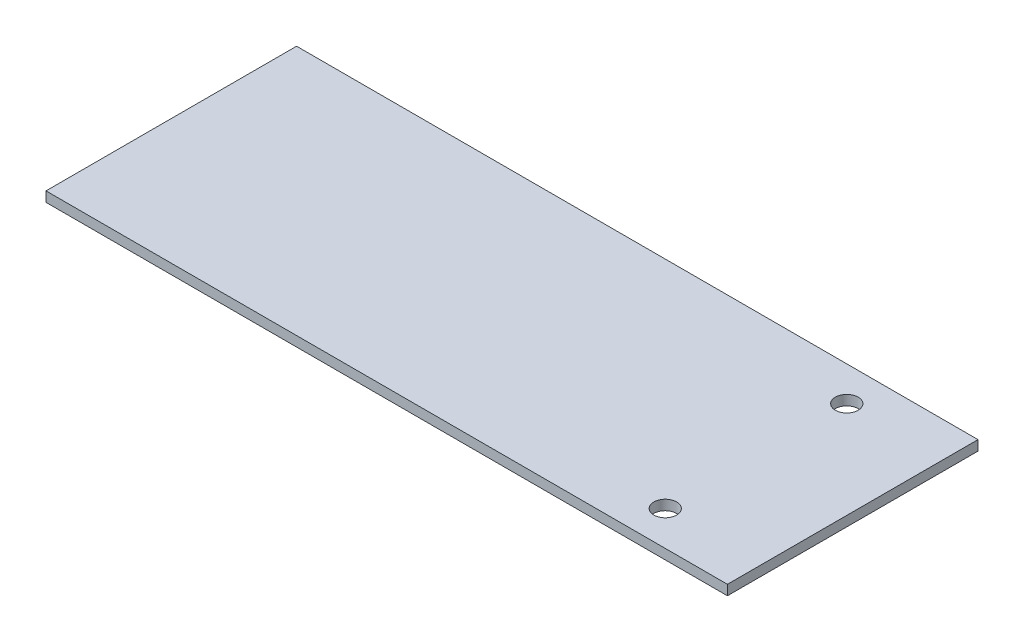
SolidWorks part; units mm, degrees
ref_plane "Front Plane" through (0, 0, 0) normal (0, 0, 1) x (1, 0, 0)
ref_plane "Top Plane" through (0, 0, 0) normal (0, 1, 0) x (1, 0, 0)
ref_plane "Right Plane" through (0, 0, 0) normal (1, 0, 0) x (0, 0, -1)
sketch "Sketch2" plane through (0, 0, 0) normal (0, 1, 0) x (1, 0, 0)
  line L1 (-56.985, -20.955) -> (56.985, -20.955)
  line L2 (-56.985, -20.955) -> (-56.985, 20.955)
  line L3 (-56.985, 20.955) -> (56.985, 20.955)
  line L4 (56.985, -20.955) -> (56.985, 20.955)
  line L5 (-56.985, -20.955) -> (56.985, 20.955) construction
  line L6 (-56.985, 20.955) -> (56.985, -20.955) construction
  point P0 (0, 0)
  dimension "D1" = 113.97
  dimension "D2" = 41.91
extrude "Boss-Extrude1" add sketch "Sketch2" along normal blind 1.67
sketch "Sketch3" plane through (0, 1.67, 0) normal (0, 1, 0) x (1, 0, 0)
  line L0 (40.8075, -15.18) -> (40.8075, 15.18) construction
  line L1 (0, 0) -> (40.8075, 0) construction
  line L4 (40.8075, 15.18) -> (56.985, 15.18) construction
  line L5 (56.985, -20.955) -> (56.985, 20.955) construction
  circle A0 centre (40.8075, 15.18) radius 1.9075
  circle A1 centre (40.8075, -15.18) radius 1.9075
  point P7 (0, 0)
  point P9 (42.9728, 15.195)
  point P11 (42.715, 15.18)
  point P13 (0, 0)
  dimension "D1" = 3.815
  dimension "D2" = 30.36
  dimension "D3" = 14.27
extrude "Cut-Extrude1" cut sketch "Sketch3" against normal through all
